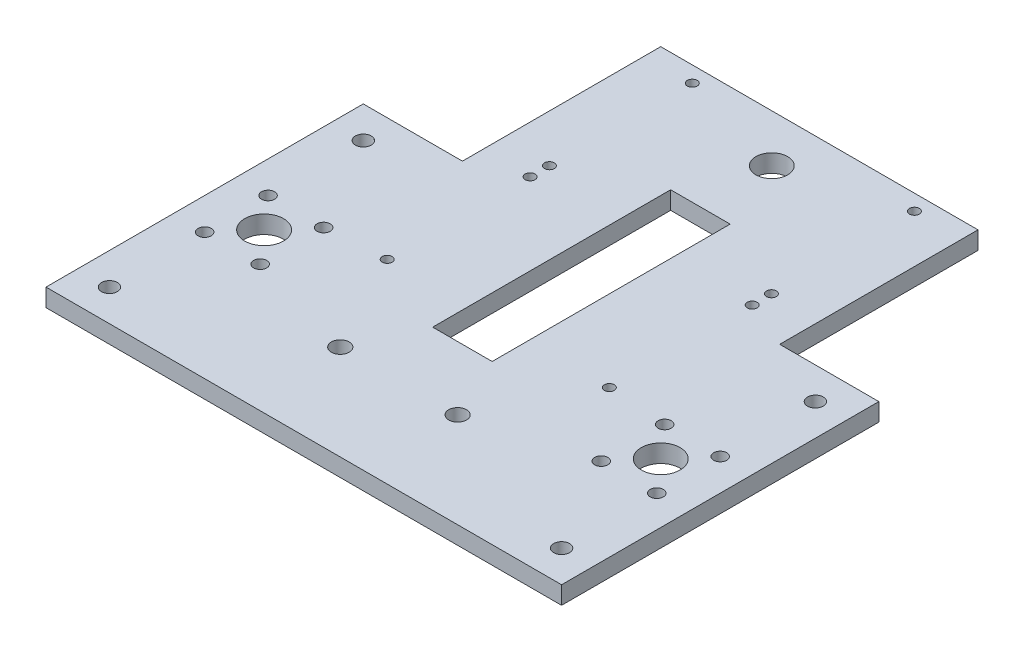
SolidWorks part; units mm, degrees
ref_plane "前视基准面" through (0, 0, 0) normal (0, 0, 1) x (1, 0, 0)
ref_plane "上视基准面" through (0, 0, 0) normal (0, 1, 0) x (1, 0, 0)
ref_plane "右视基准面" through (0, 0, 0) normal (1, 0, 0) x (0, 0, -1)
sketch "草图2" plane through (0, 0, 0) normal (0, 1, 0) x (1, 0, 0)
  line L0 (-50, 0) -> (-50, -9.5455) construction
  line L1 (-65, 40) -> (65, 40)
  line L2 (-65, 40) -> (-65, -40)
  line L3 (-65, -40) -> (65, -40)
  line L4 (65, 40) -> (65, -40)
  line L5 (-65, 40) -> (65, -40) construction
  line L6 (-65, -40) -> (65, 40) construction
  line L7 (0, 0) -> (0, 16.4747) construction
  circle A0 centre (-50, 0) radius 4.9
  circle A1 centre (-57, 8) radius 1.65
  circle A2 centre (-57, -8) radius 1.65
  circle A3 centre (-43, 8) radius 1.65
  circle A4 centre (-43, -8) radius 1.65
  circle A5 centre (43, 8) radius 1.65
  circle A6 centre (43, -8) radius 1.65
  circle A7 centre (57, -8) radius 1.65
  circle A8 centre (50, 0) radius 4.9
  circle A9 centre (57, 8) radius 1.65
  point P0 (0, 0)
  dimension "D2" = 8
  dimension "D5" = 3.3
  dimension "D6" = 3.3
  dimension "D7" = 9.8
  dimension "D8" = 50
  dimension "D1" = 8
  dimension "D3" = 7
  dimension "D4" = 7
  dimension "D9" = 130
  dimension "D10" = 80
extrude "凸台-拉伸1" add sketch "草图2" along normal blind 4.5
sketch "草图3" plane through (0, 0, 0) normal (0, -1, 0) x (1, 0, 0)
  line L0 (-65, 40) -> (65, 40) construction
  line L1 (-65, -40) -> (-65, 40) construction
  line L2 (0, 0) -> (0, 8.6232) construction
  line L3 (0, 0) -> (5.6938, 0) construction
  circle A0 centre (-57, 32) radius 2
  circle A1 centre (57, 32) radius 2
  circle A2 centre (57, -32) radius 2
  circle A3 centre (-57, -32) radius 2
  dimension "D1" = 4
  dimension "D2" = 8
  dimension "D3" = 8
extrude "切除-拉伸1" cut sketch "草图3" against normal blind 10
sketch "草图5" plane through (0, 0, 0) normal (0, -1, 0) x (1, 0, 0)
  line L0 (65, -40) -> (-65, -40) construction
  line L1 (-40, 90) -> (40, 90)
  line L2 (-40, 90) -> (-40, -90)
  line L3 (-40, -90) -> (40, -90)
  line L4 (40, 90) -> (40, -90)
  line L5 (-40, 90) -> (40, -90) construction
  line L6 (-40, -90) -> (40, 90) construction
  line L7 (65, -40) -> (-65, -40)
  point P1 (0, 0)
  line M9 (-65, -40) -> (65, -40)
  dimension "D1" = 80
  dimension "D2" = 50
extrude "凸台-拉伸2" add sketch "草图5" against normal up to surface (4.5 mm away) contours L4 L2 L3 M9 up to face at (-57, 4.5, -30)
sketch "草图6" plane through (0, 0, 0) normal (0, -1, 0) x (1, 0, 0)
  line L0 (-40, -90) -> (40, -90) construction
  circle A0 centre (0, -78) radius 4
  dimension "D1" = 8
  dimension "D2" = 12
extrude "切除-拉伸2" cut sketch "草图6" against normal blind 10
sketch "草图7" plane through (0, 0, 0) normal (0, -1, 0) x (1, 0, 0)
  circle A3 centre (-14.7951, 16) radius 2.25
  circle A5 centre (14.7951, 16) radius 2.25
  dimension "D1" = 4.5
  dimension "D2" = 4.5
extrude "切除-拉伸3" cut sketch "草图7" against normal blind 10
sketch "草图8" plane through (0, 0, 0) normal (0, -1, 0) x (1, 0, 0)
  circle A8 centre (-28.0391, -45.1013) radius 1.25
  circle A9 centre (27.9681, -45.1013) radius 1.25
  circle A10 centre (27.9178, -86.0314) radius 1.25
  circle A11 centre (-28.0391, -85.9954) radius 1.25
  dimension "D1" = 2.5
extrude "切除-拉伸4" cut sketch "草图8" against normal blind 10
sketch "草图9" plane through (0, 0, 0) normal (0, -1, 0) x (1, 0, 0)
  line L1 (-7.5, 0) -> (7.5, 0)
  line L2 (-7.5, 0) -> (-7.5, -60)
  line L3 (-7.5, -60) -> (7.5, -60)
  line L4 (7.5, 0) -> (7.5, -60)
  point P4 (0, 0)
  dimension "D1" = 15
  dimension "D2" = 60
extrude "切除-拉伸5" cut sketch "草图9" against normal blind 10
sketch "草图10" plane through (0, 0, 0) normal (0, -1, 0) x (1, 0, 0)
  line L0 (-40, -90) -> (40, -90) construction
  circle A1 centre (27.9681, -9.07) radius 1.25
  circle A3 centre (-28.0391, -9.07) radius 1.25
  circle A5 centre (-28.0391, -49.9641) radius 1.25
  circle A7 centre (27.9178, -50) radius 1.25
  dimension "D5" = 40
  dimension "D1" = 40.93
  dimension "D2" = 55.9568
  dimension "D3" = 40.8941
  dimension "D4" = 56.0071
extrude "切除-拉伸6" cut sketch "草图10" against normal blind 10
